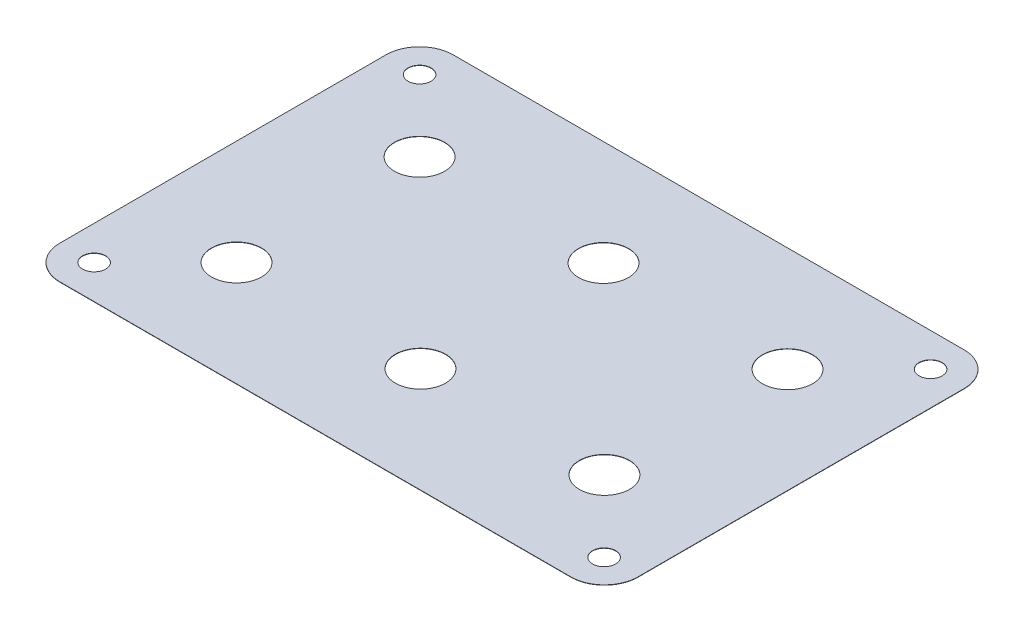
SolidWorks part; units mm, degrees
ref_plane "Front Plane" through (0, 0, 0) normal (0, 0, 1) x (1, 0, 0)
ref_plane "Top Plane" through (0, 0, 0) normal (0, 1, 0) x (1, 0, 0)
ref_plane "Right Plane" through (0, 0, 0) normal (1, 0, 0) x (0, 0, -1)
sketch "Sketch1" plane through (0, 0, 0) normal (0, 1, 0) x (1, 0, 0)
  line L0 (7739.1261, 9888.2197) -> (2313.6859, 9888.2197)
  line L1 (1956.8158, 10245.0894) -> (1956.8158, 13707.3641)
  line L2 (2313.6859, 14064.2342) -> (7739.1261, 14064.2342)
  line L3 (8095.9958, 13707.3641) -> (8095.9958, 10245.0902)
  circle A0 centre (3072.8921, 12948.1577) radius 266.4458
  circle A1 centre (5026.406, 12948.1577) radius 266.4459
  circle A2 centre (6980.1739, 12948.1577) radius 266.4458
  circle A3 centre (3072.8921, 11004.2958) radius 266.4458
  circle A4 centre (5026.406, 11004.2958) radius 266.4459
  circle A5 centre (6980.1739, 11004.2958) radius 266.4458
  circle A6 centre (2316.988, 13704.3159) radius 122.4279
  circle A7 centre (2316.988, 10248.3923) radius 122.4281
  circle A8 centre (7736.0782, 10244.5817) radius 122.4282
  circle A9 centre (7739.6338, 13707.8718) radius 122.4282
  spline S0 degree 3 poles (2313.6859, 9888.2197) (2116.5819, 9888.2197) (1956.8158, 10047.9859) (1956.8158, 10245.0894) knots 1 1 1 1 2 2 2 2
  spline S1 degree 3 poles (1956.8158, 13707.3641) (1956.8158, 13904.468) (2116.5819, 14064.2342) (2313.6859, 14064.2342) knots 3 3 3 3 4 4 4 4
  spline S2 degree 3 poles (7739.1261, 14064.2342) (7936.2303, 14064.2342) (8095.9958, 13904.4683) (8095.9958, 13707.3641) knots 5 5 5 5 6 6 6 6
  spline S3 degree 3 poles (8095.9958, 10245.0902) (8095.9958, 10047.9859) (7936.2303, 9888.2197) (7739.1261, 9888.2197) knots 7 7 7 7 8 8 8 8
extrude "Boss-Extrude1" add sketch "Sketch1" along normal blind 3.175
